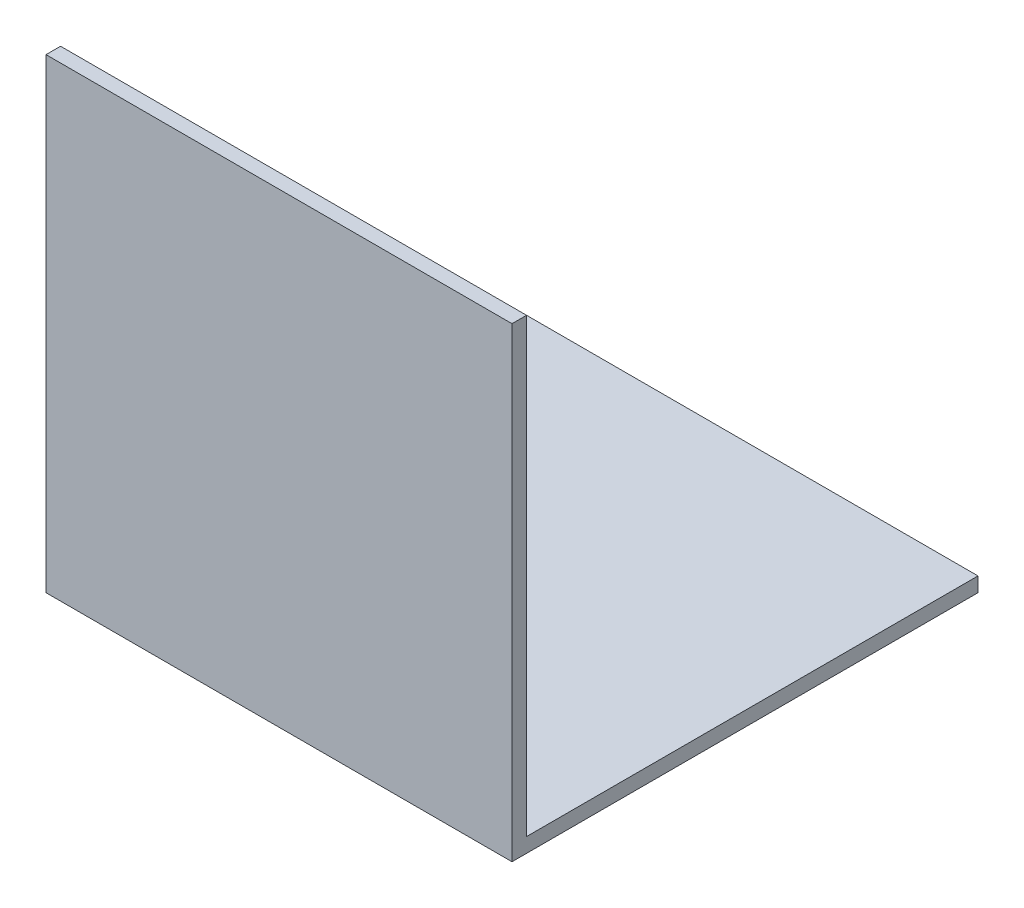
SolidWorks part; units mm, degrees
ref_plane "Front Plane" through (0, 0, 0) normal (0, 0, 1) x (1, 0, 0)
ref_plane "Top Plane" through (0, 0, 0) normal (0, 1, 0) x (1, 0, 0)
ref_plane "Right Plane" through (0, 0, 0) normal (1, 0, 0) x (0, 0, -1)
sketch "Sketch1" plane through (0, 0, 0) normal (0, 1, 0) x (1, 0, 0)
  line L1 (0, 0) -> (25.4, 0)
  line L2 (0, 0) -> (0, 25.4)
  line L3 (0, 25.4) -> (25.4, 25.4)
  line L4 (25.4, 0) -> (25.4, 25.4)
  dimension "D1" = 25.4
  dimension "D2" = 25.4
extrude "Boss-Extrude1" add sketch "Sketch1" along normal blind 0.7937
sketch "Sketch2" plane through (25.4, 0, 0) normal (1, 0, 0) x (0, 0, -1)
  line L1 (0, 0) -> (0.7937, 0)
  line L2 (0, 0) -> (0, 25.4)
  line L3 (0, 25.4) -> (0.7937, 25.4)
  line L4 (0.7937, 0) -> (0.7937, 25.4)
  dimension "D1" = 25.4
  dimension "D2" = 0.7937
extrude "Boss-Extrude2" add sketch "Sketch2" against normal blind 25.4
